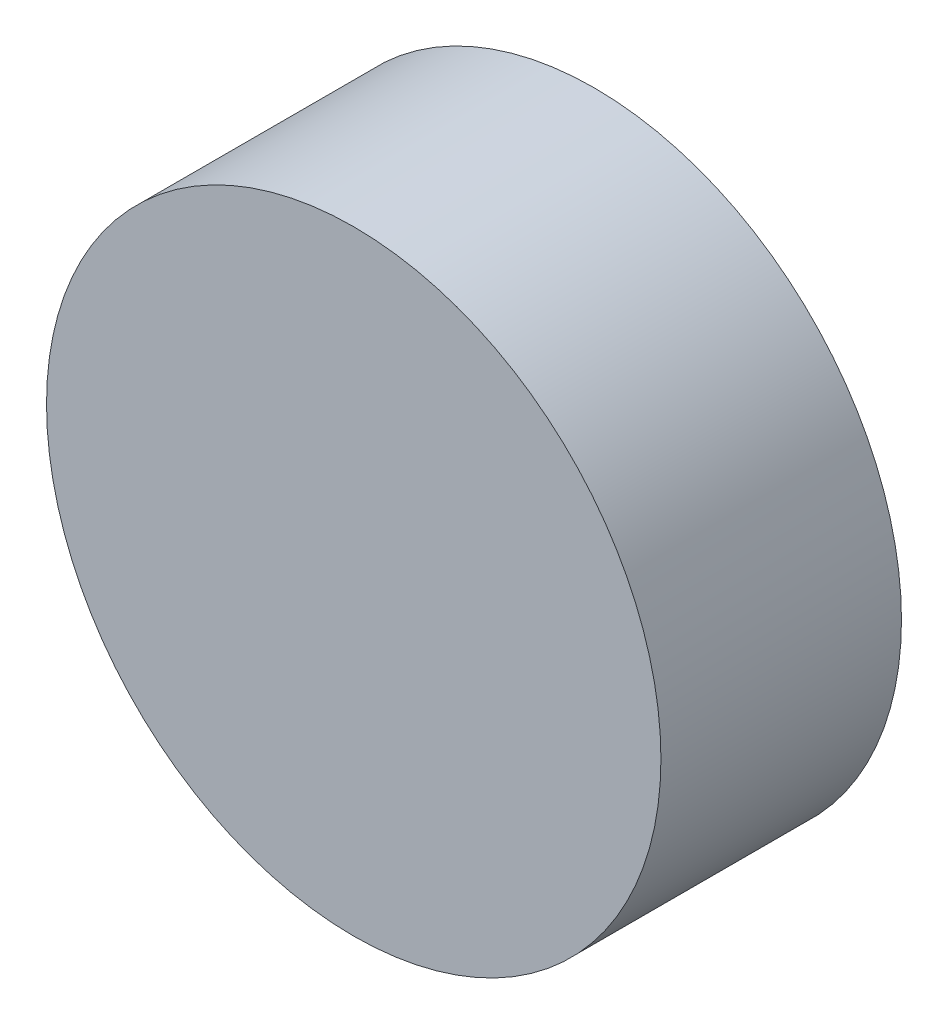
SolidWorks part; units mm, degrees
ref_plane "前视基准面" through (0, 0, 0) normal (0, 0, 1) x (1, 0, 0)
ref_plane "上视基准面" through (0, 0, 0) normal (0, 1, 0) x (1, 0, 0)
ref_plane "右视基准面" through (0, 0, 0) normal (1, 0, 0) x (0, 0, -1)
sketch "草图1" plane through (0, 0, 0) normal (0, 0, 1) x (1, 0, 0)
  circle A0 centre (0, 0) radius 53
  dimension "D1" = 106
extrude "凸台-拉伸1" add sketch "草图1" along normal blind 41.5
